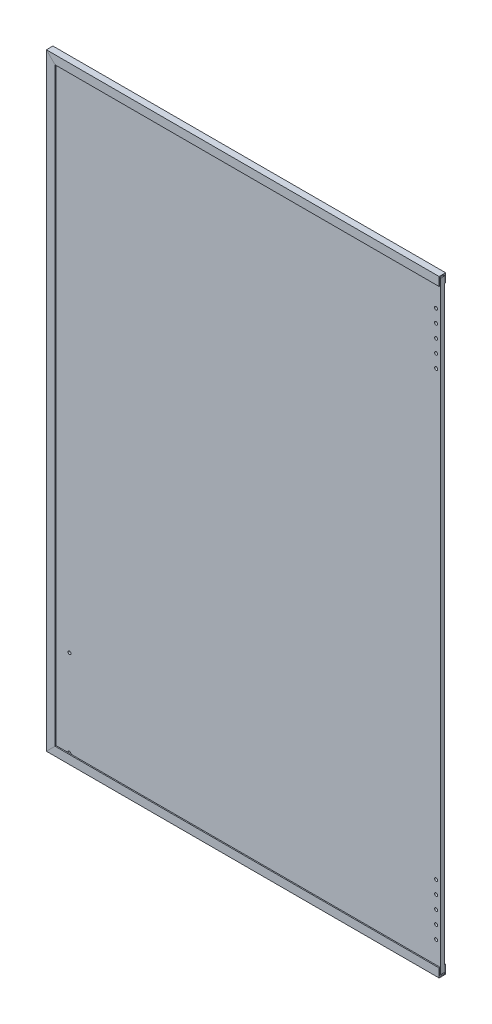
SolidWorks part; units mm, degrees
material "PC High Viscosity"
ref_plane "Front Plane" through (0, 0, 0) normal (0, 0, 1) x (1, 0, 0)
ref_plane "Top Plane" through (0, 0, 0) normal (0, 1, 0) x (1, 0, 0)
ref_plane "Right Plane" through (0, 0, 0) normal (1, 0, 0) x (0, 0, -1)
sketch "Shelf opening" plane through (0, 0, 0) normal (0, 0, 1) x (1, 0, 0)
  line L1 (0, 0) -> (577.85, 0)
  line L2 (0, 0) -> (0, 863.6)
  line L3 (0, 863.6) -> (577.85, 863.6)
  line L4 (577.85, 0) -> (577.85, 863.6)
  dimension "D1" = 577.85
  dimension "D2" = 863.6
sketch "Sketch2" plane through (0, 0, 0) normal (0, 0, 1) x (1, 0, 0)
  line L0 (577.85, 0) -> (577.85, 863.6) construction
  line L1 (3.175, 876.3) -> (577.85, 876.3)
  line L2 (3.175, 876.3) -> (3.175, -12.7)
  line L3 (3.175, -12.7) -> (577.85, -12.7)
  line L4 (577.85, 876.3) -> (577.85, -12.7)
  line L5 (0, 863.6) -> (577.85, 863.6) construction
  line L6 (0, 0) -> (0, 863.6) construction
  line L7 (0, 0) -> (577.85, 0) construction
  dimension "D1" = 12.7
  dimension "D2" = 3.175
  dimension "D3" = 12.7
extrude "Frame outer dimensions" add sketch "Sketch2" along normal mid plane 9.525
sketch "Sketch3" plane through (0, 0, 4.7625) normal (0, 0, 1) x (1, 0, 0)
  line L0 (577.85, -12.7) -> (577.85, 876.3) construction
  line L1 (577.85, 863.6) -> (15.875, 863.6)
  line L2 (577.85, 863.6) -> (577.85, 0)
  line L3 (577.85, 0) -> (15.875, 0)
  line L4 (15.875, 863.6) -> (15.875, 0)
  line L5 (577.85, 876.3) -> (3.175, 876.3) construction
  line L6 (3.175, 876.3) -> (3.175, -12.7) construction
  line L7 (3.175, -12.7) -> (577.85, -12.7) construction
  dimension "D1" = 12.7
  dimension "D2" = 12.7
  dimension "D3" = 12.7
extrude "Frame inner dimensions" cut sketch "Sketch3" against normal through all
sketch "Sketch4" plane through (0, 0, 0) normal (0, 0, 1) x (1, 0, 0)
  line L0 (577.85, 863.6) -> (577.85, 876.3) construction
  line L1 (577.85, 874.7125) -> (4.7625, 874.7125)
  line L2 (577.85, 874.7125) -> (577.85, -11.1125)
  line L3 (577.85, -11.1125) -> (4.7625, -11.1125)
  line L4 (4.7625, 874.7125) -> (4.7625, -11.1125)
  line L5 (577.85, 876.3) -> (3.175, 876.3) construction
  line L6 (3.175, 876.3) -> (3.175, -12.7) construction
  line L7 (3.175, -12.7) -> (577.85, -12.7) construction
  dimension "D1" = 1.5875
  dimension "D2" = 1.5875
  dimension "D3" = 1.5875
extrude "Frame profile" cut sketch "Sketch4" along normal offset from surface 1.5875 and the other way offset from surface (3.175 mm away) 1.5875 up to face at (293.6875, 431.8, 4.7625) other way up to face at (293.6875, 431.8, -4.7625)
sketch "Frame sections" plane through (0, 0, 4.7625) normal (0, 0, 1) x (1, 0, 0)
  line L0 (3.175, 876.3) -> (15.875, 863.6)
  line L1 (3.175, -12.7) -> (15.875, 0)
split "Frame section split" trim tools "Frame sections" bodies to split 103 resulting bodies 105 106 107
sketch "Sketch5" plane through (0, 0, 0) normal (0, 0, 1) x (1, 0, 0)
  line L0 (577.85, 863.6) -> (577.85, 876.3) construction
  line L1 (577.85, 873.125) -> (6.35, 873.125)
  line L2 (577.85, 873.125) -> (577.85, -9.525)
  line L3 (577.85, -9.525) -> (6.35, -9.525)
  line L4 (6.35, 873.125) -> (6.35, -9.525)
  line L5 (4.7625, 874.7125) -> (577.85, 874.7125) construction
  line L6 (4.7625, -11.1125) -> (4.7625, 874.7125) construction
  line L7 (577.85, -11.1125) -> (4.7625, -11.1125) construction
  dimension "D1" = 1.5875
  dimension "D2" = 1.5875
  dimension "D3" = 1.5875
  dimension "D4" = 571.5
  dimension "D5" = 882.65
extrude "Door panel" add sketch "Sketch5" along normal mid plane 5.588 separate body
sketch "Hinge positions" plane through (0, 0, 2.794) normal (0, 0, 1) x (1, 0, 0)
  line L0 (577.85, -9.525) -> (577.85, 873.125) construction
  line L1 (577.85, 841.375) -> (565.15, 841.375)
  line L2 (577.85, 841.375) -> (577.85, 746.125)
  line L3 (577.85, 746.125) -> (565.15, 746.125)
  line L4 (565.15, 841.375) -> (565.15, 746.125)
  line L5 (565.15, 117.475) -> (577.85, 117.475)
  line L6 (565.15, 117.475) -> (565.15, 22.225)
  line L7 (565.15, 22.225) -> (577.85, 22.225)
  line L8 (577.85, 117.475) -> (577.85, 22.225)
  line L10 (0, 0) -> (577.85, 0) construction
  line L11 (0, 863.6) -> (577.85, 863.6) construction
  dimension "D1" = 95.25
  dimension "D2" = 12.7
  dimension "D3" = 22.225
  dimension "D4" = 22.225
  dimension "D5" = 723.9
sketch "Sketch8" plane through (0, 0, 2.794) normal (0, 0, 1) x (1, 0, 0)
  line L0 (565.15, 69.85) -> (577.85, 69.85) construction
  line L2 (565.15, 117.475) -> (565.15, 22.225) construction
  line L3 (577.85, 117.475) -> (577.85, 22.225) construction
  line L4 (565.15, 793.75) -> (577.85, 793.75) construction
  line L6 (565.15, 841.375) -> (565.15, 746.125) construction
  line L7 (577.85, 841.375) -> (577.85, 746.125) construction
  point P0 (571.5, 31.75)
  point P11 (571.5, 50.8)
  point P12 (571.5, 69.85)
  point P13 (571.5, 88.9)
  point P14 (571.5, 107.95)
  point P15 (571.5, 774.7)
  point P16 (571.5, 793.75)
  point P17 (571.5, 812.8)
  point P18 (571.5, 831.85)
  point P19 (571.5, 755.65)
  dimension "D3" = 19.05
  dimension "D1" = 5
  dimension "D2" = 2
hole_wizard "#8 Clearance Hole1" positions "Sketch8" profile "Sketch9" hole size "#8" standard "ANSI Inch" end condition through all
sketch "Sketch9" plane through (571.5, 31.75, 2.794) normal (1, 0, 0) x (0, -1, 0)
  line L0 (0, 0) -> (0, 7.5565)
  line L1 (0, 7.5565) -> (2.2479, 7.5565)
  line L2 (2.2479, 7.5565) -> (2.2479, 0)
  line L5 (2.2479, 0) -> (0, 0)
  line L11 (0, -6.35) -> (0, 107.95) construction
  dimension "Thru Hole Dia." = 4.4958
  dimension "Thru Hole Depth" = 7.5565
sketch "Handle position" plane through (0, 0, 2.794) normal (0, 0, 1) x (1, 0, 0)
  line L0 (6.35, 873.125) -> (6.35, -9.525) construction
  line L1 (6.35, 139.7) -> (44.45, 139.7)
  line L2 (6.35, 139.7) -> (6.35, -9.525)
  line L3 (6.35, -9.525) -> (44.45, -9.525)
  line L4 (44.45, 139.7) -> (44.45, -9.525)
  line L5 (6.35, -9.525) -> (577.85, -9.525) construction
  dimension "D1" = 149.225
  dimension "D2" = 38.1
sketch "Sketch11" plane through (0, 0, 2.794) normal (0, 0, 1) x (1, 0, 0)
  line L0 (34.925, 127) -> (34.925, 0) construction
  line L2 (6.35, 139.7) -> (6.35, -9.525) construction
  line L3 (6.35, -9.525) -> (44.45, -9.525) construction
  point P0 (34.925, 0)
  point P2 (34.925, 127)
  dimension "D1" = 28.575
  dimension "D2" = 9.525
  dimension "D3" = 136.525
hole_wizard "#8 Clearance Hole2" positions "Sketch11" profile "Sketch12" hole size "#8" standard "ANSI Inch" end condition through all
sketch "Sketch12" plane through (34.925, 0, 2.794) normal (1, 0, 0) x (0, -1, 0)
  line L0 (0, 0) -> (0, 7.5565)
  line L1 (0, 7.5565) -> (2.2479, 7.5565)
  line L2 (2.2479, 7.5565) -> (2.2479, 0)
  line L5 (2.2479, 0) -> (0, 0)
  line L11 (0, -6.35) -> (0, 107.95) construction
  dimension "Thru Hole Dia." = 4.4958
  dimension "Thru Hole Depth" = 7.5565
mirror "Mirror1" about plane through (0, 0, 0) normal (1, 0, 0) of bodies 105 106 107 113 108
delete or keep bodies "Body-Delete/Keep 1" type keep bodies bodies 105 106 107 113
delete or keep bodies "Body-Delete/Keep 2" [suppressed] type keep bodies bodies 109 110 111 112
